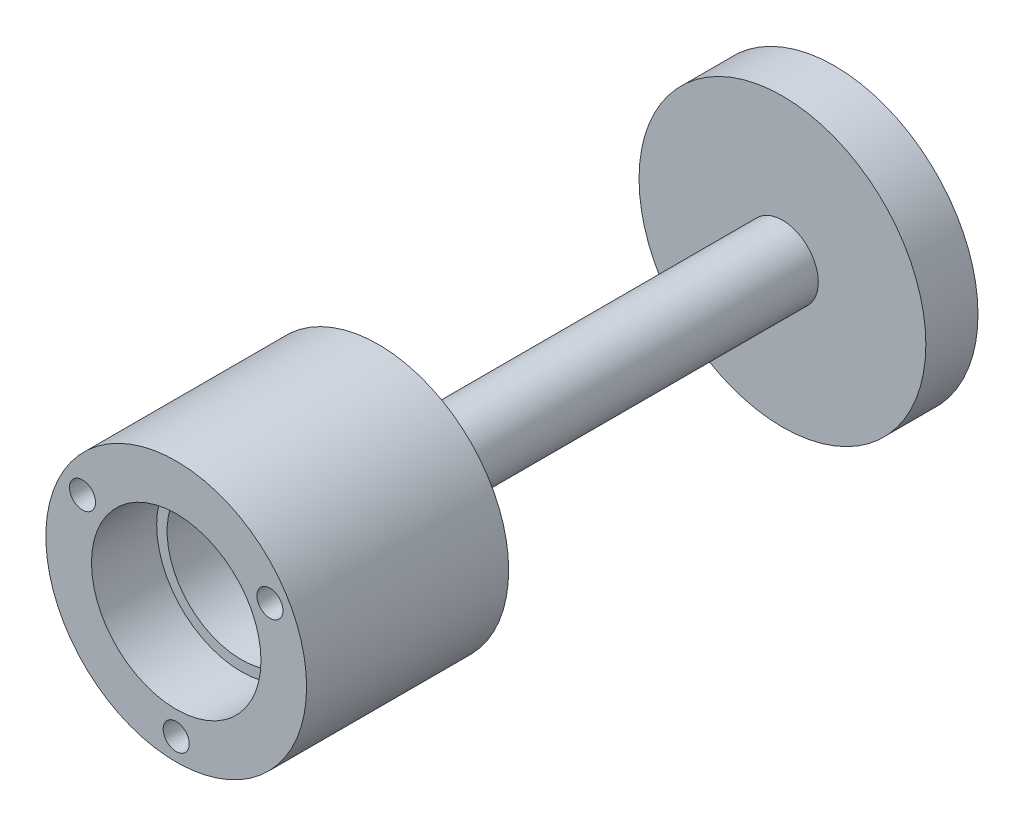
SolidWorks part; units mm, degrees
material "AISI 4340 Steel, normalized"
ref_plane "Front Plane" through (0, 0, 0) normal (0, 0, 1) x (1, 0, 0)
ref_plane "Top Plane" through (0, 0, 0) normal (0, 1, 0) x (1, 0, 0)
ref_plane "Right Plane" through (0, 0, 0) normal (1, 0, 0) x (0, 0, -1)
sketch "Sketch1" plane through (0, 0, 0) normal (0, 0, 1) x (1, 0, 0)
  circle A0 centre (0, 0) radius 11
extrude "Mounting_Flange" add sketch "Sketch1" along normal blind 4 from offset 4
sketch "Sketch2" plane through (0, 0, 0) normal (0, 0, 1) x (1, 0, 0)
  circle A0 centre (0, 0) radius 2.75
extrude "D5p5_Central_Post" add sketch "Sketch2" along normal blind 31.01
sketch "Sketch3" plane through (0, 0, 0) normal (0, 0, 1) x (1, 0, 0)
  circle A0 centre (0, 0) radius 10
extrude "Closed_Floor_Below_Shaft_Nose" add sketch "Sketch3" along normal blind 2 from offset 31
sketch "Sketch4" plane through (0, 0, 0) normal (0, 0, 1) x (1, 0, 0)
  circle A0 centre (0, 0) radius 10
  circle A1 centre (0, 0) radius 5.7
extrude "Shaft_And_Clip_Clearance" add sketch "Sketch4" along normal blind 8.5 from offset 33
sketch "Sketch5" plane through (0, 0, 0) normal (0, 0, 1) x (1, 0, 0)
  circle A0 centre (0, 0) radius 10
  circle A1 centre (0, 0) radius 6.5
extrude "Lower_686ZZ_Seat" add sketch "Sketch5" along normal blind 5 from offset 41.5
sketch "Sketch6" plane through (0, 0, -4) normal (0, 0, -1) x (-1, 0, 0)
  circle A0 centre (-7.188, 4.15) radius 1
  circle A1 centre (7.188, 4.15) radius 1
  circle A2 centre (0, -8.3) radius 1
extrude "Base_Three_M2_Blind_Thread_Major_Envelopes" cut sketch "Sketch6" against normal blind 3.6
sketch "Sketch7" plane through (0, 0, 46.5) normal (0, 0, 1) x (1, 0, 0)
  circle A0 centre (7.188, 4.15) radius 1
  circle A1 centre (-7.188, 4.15) radius 1
  circle A2 centre (0, -8.3) radius 1
extrude "Top_Cap_Three_M2_Blind_Thread_Major_Envelopes" cut sketch "Sketch7" against normal blind 4.3
